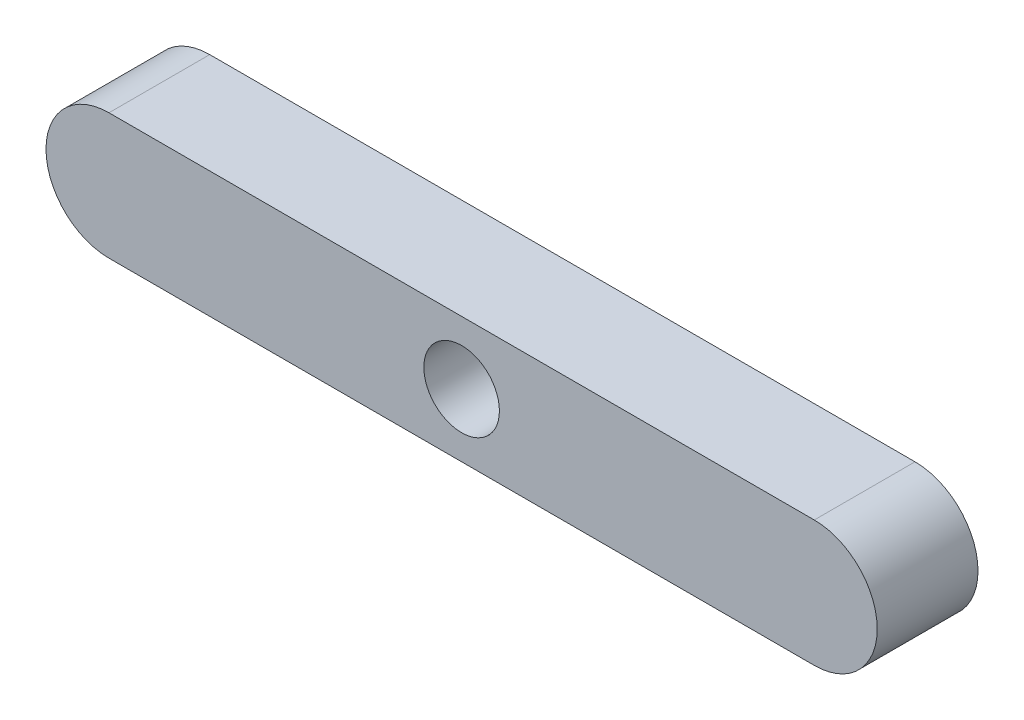
SolidWorks part; units mm, degrees
ref_plane "Alzado" through (0, 0, 0) normal (0, 0, 1) x (1, 0, 0)
ref_plane "Planta" through (0, 0, 0) normal (0, 1, 0) x (1, 0, 0)
ref_plane "Vista lateral" through (0, 0, 0) normal (1, 0, 0) x (0, 0, -1)
sketch "Croquis1" plane through (0, 0, 0) normal (0, 0, 1) x (1, 0, 0)
  line L0 (0, 0) -> (7, 0)
  line L1 (7, 0) -> (-7, 0)
  line L2 (-7, -2.5) -> (7, -2.5)
  line L3 (0, 0) -> (0, -2.5) construction
  arc A0 (-7, 0) -> (-7, -2.5) centre (-7, -1.25) ccw
  arc A3 (7, 0) -> (7, -2.5) centre (7, -1.25) cw
  point P10 (0, 0)
  dimension "D1" = 14
  dimension "D2" = 2.5
  dimension "D3" = 14
extrude "Saliente-Extruir1" add sketch "Croquis1" along normal blind 2 contours L3 L1 A0 L2 | L0 L3 L2 A3
sketch "Croquis2" plane through (0, 0, 2) normal (0, 0, 1) x (1, 0, 0)
  line L0 (0, 0) -> (0, -2.5) construction
  line L1 (-7, -2.5) -> (7, -2.5) construction
  circle A1 centre (0, -1.25) radius 0.75
  dimension "D1" = 1.5
extrude "Cortar-Extruir1" cut sketch "Croquis2" against normal blind 2
